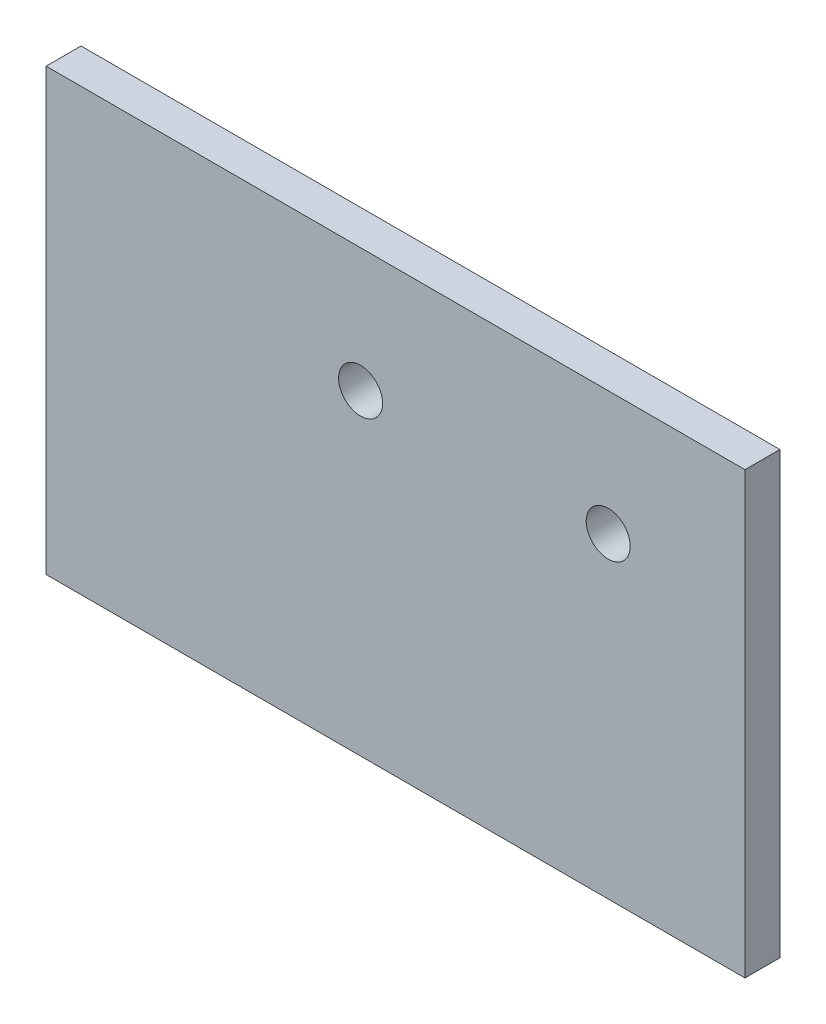
SolidWorks part; units mm, degrees
ref_plane "Front Plane" through (0, 0, 0) normal (0, 0, 1) x (1, 0, 0)
ref_plane "Top Plane" through (0, 0, 0) normal (0, 1, 0) x (1, 0, 0)
ref_plane "Right Plane" through (0, 0, 0) normal (1, 0, 0) x (0, 0, -1)
sketch "Sketch1" plane through (0, 0, 0) normal (0, 0, 1) x (1, 0, 0)
  line L1 (0, 0) -> (127, 0)
  line L2 (0, 0) -> (0, -80)
  line L3 (0, -80) -> (127, -80)
  line L4 (127, 0) -> (127, -80)
  circle A1 centre (57.15, -22.5) radius 4
  circle A2 centre (102.15, -22.5) radius 4
  point P9 (0, 0)
  dimension "D6" = 8
  dimension "D3" = 22.5
  dimension "D4" = 8
  dimension "D5" = 57.15
  dimension "D1" = 80
  dimension "D2" = 127
  dimension "D7" = 45
extrude "Boss-Extrude1" add sketch "Sketch1" along normal blind 6.35
